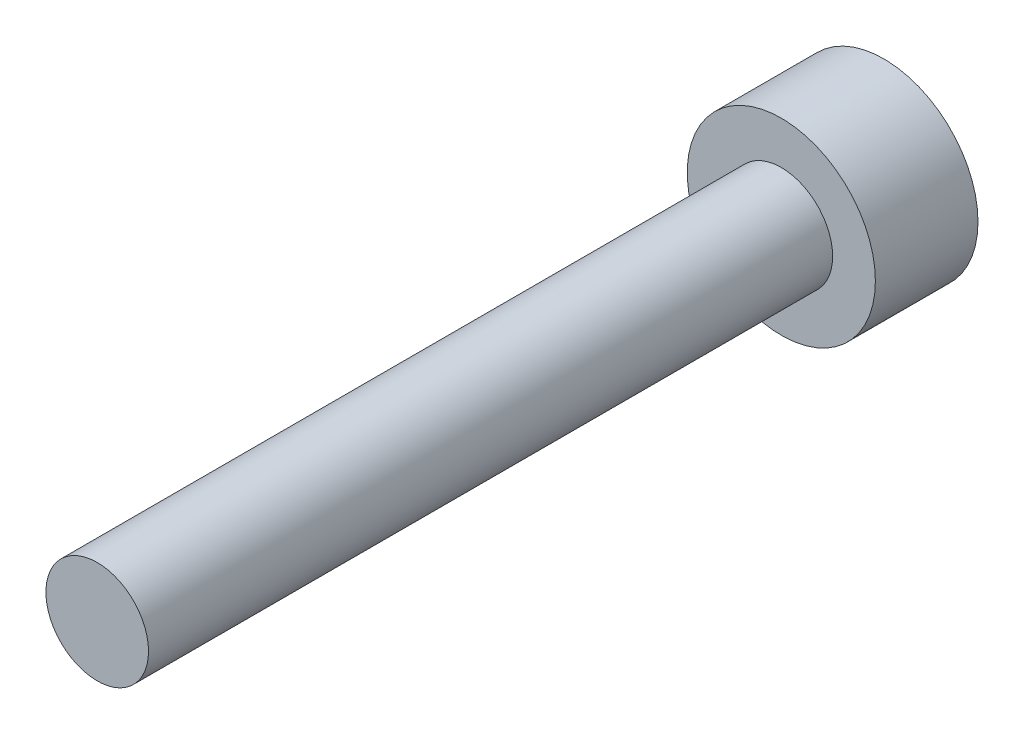
SolidWorks part; units mm, degrees
material "Acero aleado"
ref_plane "Alzado" through (0, 0, 0) normal (0, 0, 1) x (1, 0, 0)
ref_plane "Planta" through (0, 0, 0) normal (0, 1, 0) x (1, 0, 0)
ref_plane "Vista lateral" through (0, 0, 0) normal (1, 0, 0) x (0, 0, -1)
sketch "Croquis1" plane through (0, 0, 0) normal (0, 0, 1) x (1, 0, 0)
  circle A0 centre (0, 0) radius 2.75
  dimension "D1" = 5.5
extrude "Cabeza" add sketch "Croquis1" along normal blind 3 from offset 3
sketch "Croquis2" plane through (0, 0, 0) normal (0, 0, 1) x (1, 0, 0)
  circle A0 centre (0, 0) radius 1.5
  dimension "D1" = 3
extrude "Cuerpo" add sketch "Croquis2" along normal blind 20
sketch "Croquis3" plane through (0, 0, 0) normal (0, 0, 1) x (1, 0, 0)
  line L0 (1.4434, 0) -> (0.7217, 1.25)
  line L1 (0.7217, 1.25) -> (-0.7217, 1.25)
  line L2 (-0.7217, 1.25) -> (-1.4434, 0)
  line L3 (-1.4434, 0) -> (-0.7217, -1.25)
  line L4 (-0.7217, -1.25) -> (0.7217, -1.25)
  line L5 (0.7217, -1.25) -> (1.4434, 0)
  dimension "D1" = 1.4434
  dimension "D2" = 0.7217
  dimension "D3" = 1.25
  dimension "D4" = 0.7217
  dimension "D5" = 1.25
  dimension "D6" = 1.4434
  dimension "D7" = 0.7217
  dimension "D8" = 1.25
  dimension "D9" = 0.7217
  dimension "D10" = 1.25
extrude "Hexagono_interior" cut sketch "Croquis3" along normal blind 1.3 from offset 3
